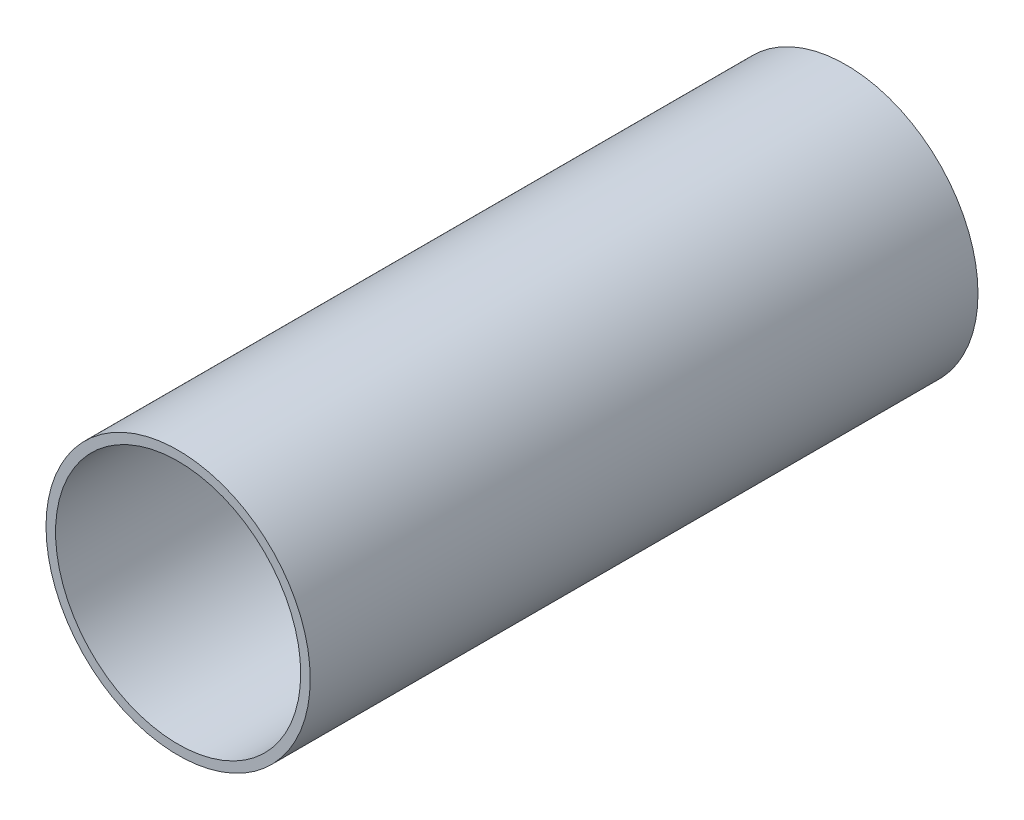
SolidWorks part; units mm, degrees
material "AISI 1020"
ref_plane "Plano superior" through (0, 0, 0) normal (0, 0, 1) x (1, 0, 0)
ref_plane "Plano frontal" through (0, 0, 0) normal (0, 1, 0) x (1, 0, 0)
ref_plane "Plano direito" through (0, 0, 0) normal (1, 0, 0) x (0, 0, -1)
sketch "Esboço1" plane through (0, 0, 0) normal (0, 1, 0) x (1, 0, 0)
  line L0 (0, 0) -> (0, 96.0208) construction
  line L1 (25.7, 0) -> (25.7, 140)
  line L2 (25.7, 140) -> (27.7, 140)
  line L3 (27.7, 140) -> (27.7, 0)
  line L4 (27.7, 0) -> (25.7, 0)
  dimension "D1" = 25.7
  dimension "D2" = 2
  dimension "D3" = 140
revolve "Revolução2" add sketch "Esboço1" angle 360 about L0
